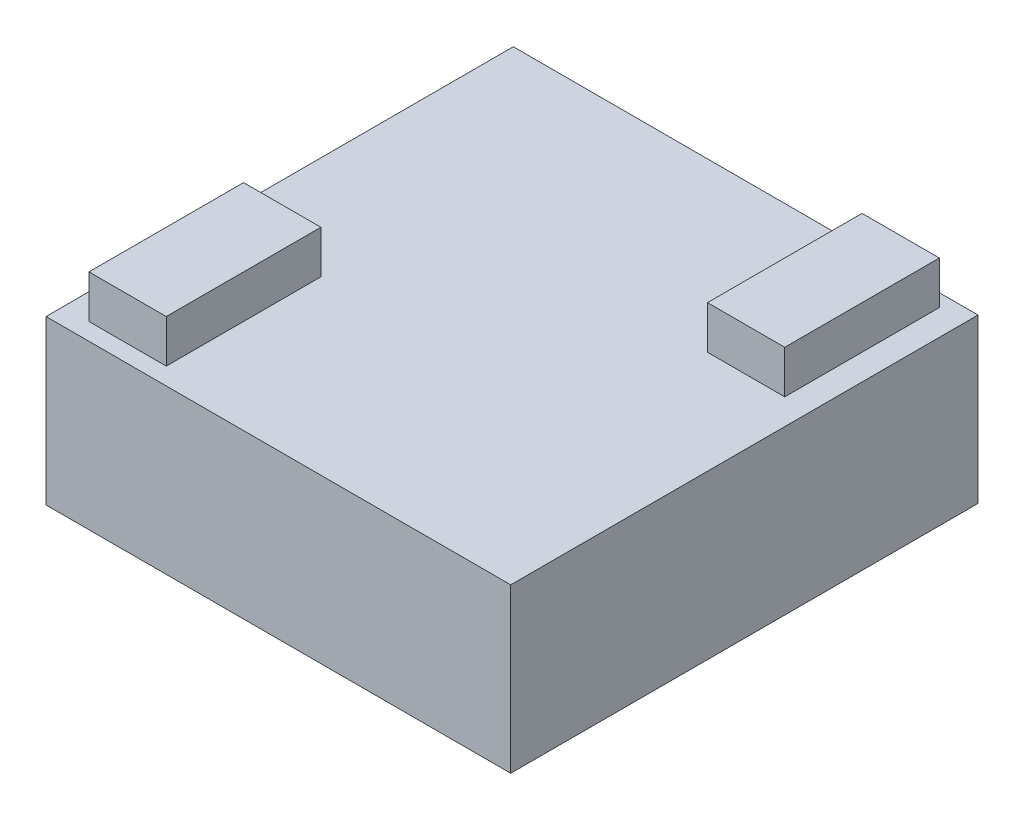
SolidWorks part; units mm, degrees
material "Epoxy, renforcé"
ref_plane "Plan de face" through (0, 0, 0) normal (0, 0, 1) x (1, 0, 0)
ref_plane "Plan de dessus" through (0, 0, 0) normal (0, 1, 0) x (1, 0, 0)
ref_plane "Plan de droite" through (0, 0, 0) normal (1, 0, 0) x (0, 0, -1)
sketch "Esquisse1" plane through (0, 0, 0) normal (0, 1, 0) x (1, 0, 0)
  line L1 (0, 0) -> (54.1, 0)
  line L2 (0, 0) -> (0, 54.4)
  line L3 (0, 54.4) -> (54.1, 54.4)
  line L4 (54.1, 0) -> (54.1, 54.4)
  dimension "D1" = 54.4
  dimension "D2" = 54.1
extrude "Boss.-Extru.1" add sketch "Esquisse1" along normal blind 19
sketch "Esquisse2" plane through (0, 0, 0) normal (0, -1, 0) x (1, 0, 0)
  line L0 (0, -54.4) -> (0, 0) construction
  line L1 (17, -34.4) -> (37, -34.4)
  line L2 (17, -34.4) -> (17, -22.4)
  line L3 (17, -22.4) -> (37, -22.4)
  line L4 (37, -34.4) -> (37, -22.4)
  line L5 (54.1, -54.4) -> (0, -54.4) construction
  point P4 (27, -34.4)
  point P7 (37, -28.4)
  dimension "D1" = 20
  dimension "D2" = 12
  dimension "D3" = 27
  dimension "D4" = 26
extrude "Boss.-Extru.2" add sketch "Esquisse2" along normal blind 15
sketch "Esquisse3" plane through (0, 19, 0) normal (0, 1, 0) x (1, 0, 0)
  line L0 (0, 0) -> (54.1, 0) construction
  line L1 (42.1, 52.9) -> (51.1, 52.9)
  line L2 (42.1, 52.9) -> (42.1, 34.9)
  line L3 (42.1, 34.9) -> (51.1, 34.9)
  line L4 (51.1, 52.9) -> (51.1, 34.9)
  line L5 (3, 20) -> (12, 20)
  line L6 (3, 20) -> (3, 2)
  line L7 (3, 2) -> (12, 2)
  line L8 (12, 20) -> (12, 2)
  line L9 (54.1, 54.4) -> (0, 54.4) construction
  line L10 (54.1, 0) -> (54.1, 54.4) construction
  line L11 (0, 54.4) -> (0, 0) construction
  dimension "D1" = 18
  dimension "D2" = 2
  dimension "D3" = 1.5
  dimension "D4" = 3
  dimension "D5" = 9
  dimension "D6" = 3
extrude "Boss.-Extru.3" add sketch "Esquisse3" along normal blind 5
